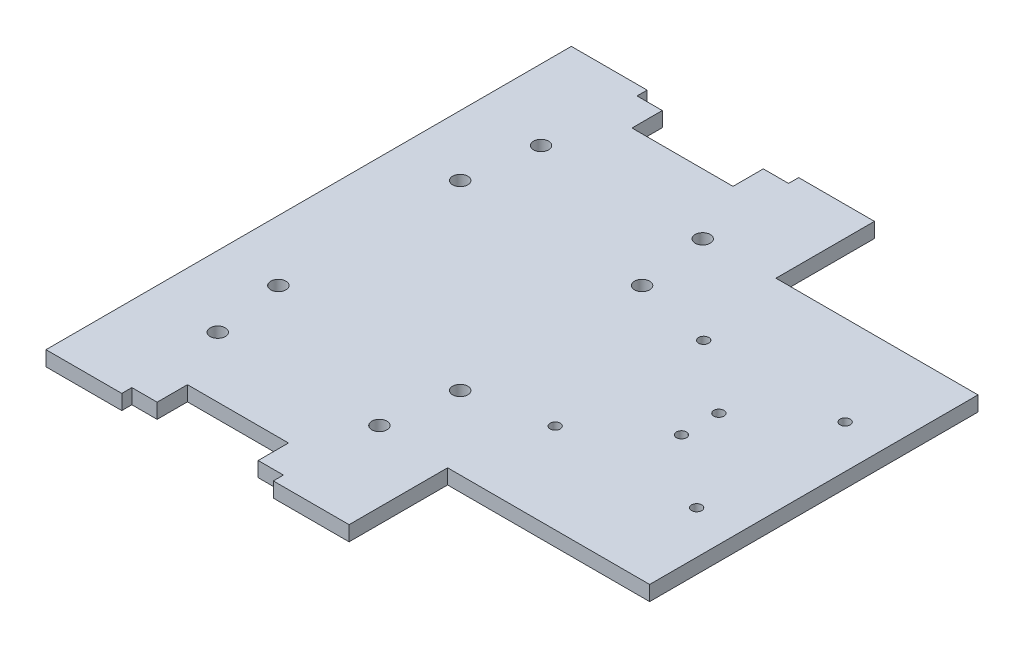
SolidWorks part; units mm, degrees
ref_plane "前视基准面" through (0, 0, 0) normal (0, 0, 1) x (1, 0, 0)
ref_plane "上视基准面" through (0, 0, 0) normal (0, 1, 0) x (1, 0, 0)
ref_plane "右视基准面" through (0, 0, 0) normal (1, 0, 0) x (0, 0, -1)
other "Configuration Table"
sketch "草图1" plane through (0, 0, 0) normal (0, 1, 0) x (1, 0, 0)
  line L3 (25, 50) -> (20, 50)
  line L5 (-20, 50) -> (-20, 52)
  line L6 (-20, 52) -> (-5, 52)
  line L7 (40, 32.5) -> (70, 32.5)
  line L8 (80, 30) -> (80, -30)
  line L9 (40, 32.5) -> (40, 50)
  line L13 (40, 50) -> (40, 52)
  line L14 (40, 52) -> (25, 52)
  line L15 (25, 52) -> (25, 50)
  line L16 (-20, 50) -> (-20, -50)
  line L17 (-5, 52) -> (-5, 50)
  line L24 (80, 30) -> (80, 32.5)
  line L27 (80, 0) -> (76.7321, 0) construction
  line L28 (70, -32.5) -> (80, -32.5)
  line L38 (70, 32.5) -> (80, 32.5)
  line L39 (80, -30) -> (80, -32.5)
  line L40 (-5, -52) -> (-5, -50)
  line L41 (25, -52) -> (25, -50)
  line L42 (40, -52) -> (25, -52)
  line L43 (40, -50) -> (40, -52)
  line L44 (40, -32.5) -> (40, -50)
  line L45 (40, -32.5) -> (70, -32.5)
  line L46 (-20, -52) -> (-5, -52)
  line L47 (-20, -50) -> (-20, -52)
  line L48 (25, -50) -> (20, -50)
  line L49 (20, -44) -> (20, -50)
  line L50 (0, 44) -> (20, 44)
  line L51 (20, 44) -> (20, 50)
  line L52 (0, 44) -> (0, 50)
  line L53 (0, 50) -> (-5, 50)
  line L54 (0, -44) -> (20, -44)
  line L55 (0, -44) -> (0, -50)
  line L56 (0, -50) -> (-5, -50)
  line L57 (10, 0) -> (10, -42.5) construction
  circle A3 centre (71.5, 14.7) radius 1
  circle A4 centre (43.5, 14.7) radius 1
  circle A5 centre (57.5, 3.7) radius 1
  circle A6 centre (26, 32) radius 1.5
  circle A9 centre (-6, 32) radius 1.5
  circle A10 centre (28, 18) radius 1.5
  circle A11 centre (-8, 18) radius 1.5
  circle A12 centre (-8, -18) radius 1.5
  circle A13 centre (28, -18) radius 1.5
  circle A14 centre (-6, -32) radius 1.5
  circle A15 centre (26, -32) radius 1.5
  circle A16 centre (57.5, -3.7) radius 1
  circle A17 centre (43.5, -14.7) radius 1
  circle A18 centre (71.5, -14.7) radius 1
  point P0 (0, 0)
  point P35 (-20, 0)
  point P45 (10, 0)
  point P53 (10, 0)
  point P55 (80, 0)
extrude "凸台-拉伸1" add sketch "草图1" along normal blind 2.95
